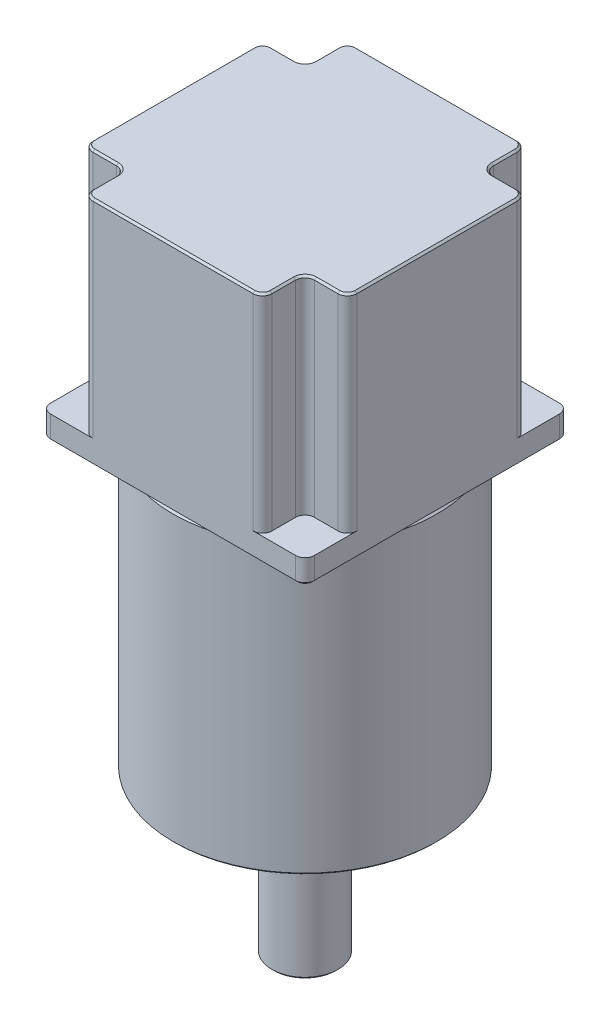
SolidWorks part; units mm, degrees
ref_plane "Front Plane" through (0, 0, 0) normal (0, 0, 1) x (1, 0, 0)
ref_plane "Top Plane" through (0, 0, 0) normal (0, 1, 0) x (1, 0, 0)
ref_plane "Right Plane" through (0, 0, 0) normal (1, 0, 0) x (0, 0, -1)
sketch "Sketch1" plane through (0, 0, 0) normal (0, 1, 0) x (1, 0, 0)
  line L1 (-28, -28) -> (28, -28)
  line L2 (-28, -28) -> (-28, 28)
  line L3 (-28, 28) -> (28, 28)
  line L4 (28, -28) -> (28, 28)
  line L5 (-28, -28) -> (28, 28) construction
  line L6 (-28, 28) -> (28, -28) construction
  point P0 (0, 0)
  dimension "D1" = 56
extrude "Boss-Extrude1" add sketch "Sketch1" along normal blind 5
sketch "Sketch2" plane through (0, 5, 0) normal (0, 1, 0) x (1, 0, 0)
  line L0 (-28, 19) -> (-19, 19)
  line L1 (-28, 28) -> (-28, -28) construction
  line L2 (-19, 19) -> (-19, 28)
  line L3 (28, 28) -> (-28, 28) construction
  line L4 (-19, 28) -> (19, 28)
  line L5 (19, 28) -> (19, 19)
  line L6 (19, 19) -> (28, 19)
  line L7 (28, -28) -> (28, 28) construction
  line L8 (28, 19) -> (28, -19)
  line L9 (-28, 19) -> (-28, -19)
  line L10 (0, 28) -> (0, 0) construction
  line L11 (0, 0) -> (28, 0) construction
  line L12 (28, 19) -> (28, 0)
  line L13 (-28, 19) -> (-28, 0)
  line L14 (-19, 19) -> (-28, 19)
  line L15 (-19, 28) -> (-19, 19)
  line L16 (19, 19) -> (19, 28)
  line L17 (28, 19) -> (19, 19)
  line L18 (28, -19) -> (19, -19)
  line L19 (19, -19) -> (19, -28)
  line L20 (-19, -28) -> (-19, -19)
  line L21 (-19, -19) -> (-28, -19)
  line L22 (19, -19) -> (28, -19)
  line L23 (19, -28) -> (19, -19)
  line L24 (-19, -28) -> (19, -28)
  line L25 (-19, -19) -> (-19, -28)
  line L26 (-28, -19) -> (-19, -19)
  line M10 (28, -28) -> (28, 28)
  line M11 (28, 28) -> (-28, 28)
  line M12 (-28, 28) -> (-28, -28)
  line M13 (-28, -28) -> (28, -28)
  dimension "D1" = 38
  dimension "D2" = 19
extrude "Boss-Extrude2" add sketch "Sketch2" along normal blind 44 contours L21 L20 L19 L18 L8 L6 L5 L2 L0 L9 M13 M10 M11 M12
fillet "Fillet1" radius 2 16 edges at (-28, 2.5, 28) (-19, 27, 28) (-19, 27, 19) (-28, 27, 19) (19, 27, 19) (19, 27, 28) (28, 27, 19) (28, 2.5, 28) (28, 27, -19) (19, 27, -19) (19, 27, -28) (28, 2.5, -28) (-19, 27, -19) (-19, 27, -28) (-28, 2.5, -28) (-28, 27, -19)
chamfer "Chamfer1" distance 0.4 angle 45 32 edges at (28, 0, 0) (27.4142, 0, -27.4142) (27.4142, 0, 27.4142) (0, 0, -28) (0, 0, 28) (-27.4142, 0, -27.4142) (-27.4142, 0, 27.4142) (-28, 0, 0) (28, 49, 0) (27.4142, 49, -18.4142) (27.4142, 49, 18.4142) (23.5, 49, -19) (23.5, 49, 19) (19.5858, 49, -19.5858) (19.5858, 49, 19.5858) (19, 49, -23.5) (19, 49, 23.5) (18.4142, 49, -27.4142) (18.4142, 49, 27.4142) (0, 49, -28) (0, 49, 28) (-18.4142, 49, -27.4142) (-18.4142, 49, 27.4142) (-19, 49, -23.5) (-19, 49, 23.5) (-19.5858, 49, -19.5858) (-19.5858, 49, 19.5858) (-23.5, 49, -19) (-23.5, 49, 19) (-27.4142, 49, -18.4142) (-27.4142, 49, 18.4142) (-28, 49, 0)
sketch "Sketch3" plane through (0, 0, 0) normal (0, -1, 0) x (1, 0, 0)
  circle A0 centre (0, 0) radius 28
extrude "Boss-Extrude3" add sketch "Sketch3" along normal blind 61 separate body
chamfer "Chamfer2" distance 0.4 angle 45 2 edges at (0, 0, -28) (0, -61, -28)
sketch "Sketch4" plane through (0, -61, 0) normal (0, -1, 0) x (1, 0, 0)
  circle A0 centre (0, 0) radius 7
  dimension "D1" = 14
extrude "Boss-Extrude4" add sketch "Sketch4" along normal blind 34 separate body
chamfer "Chamfer3" distance 0.4 angle 45 1 edges at (0, -95, -7)
